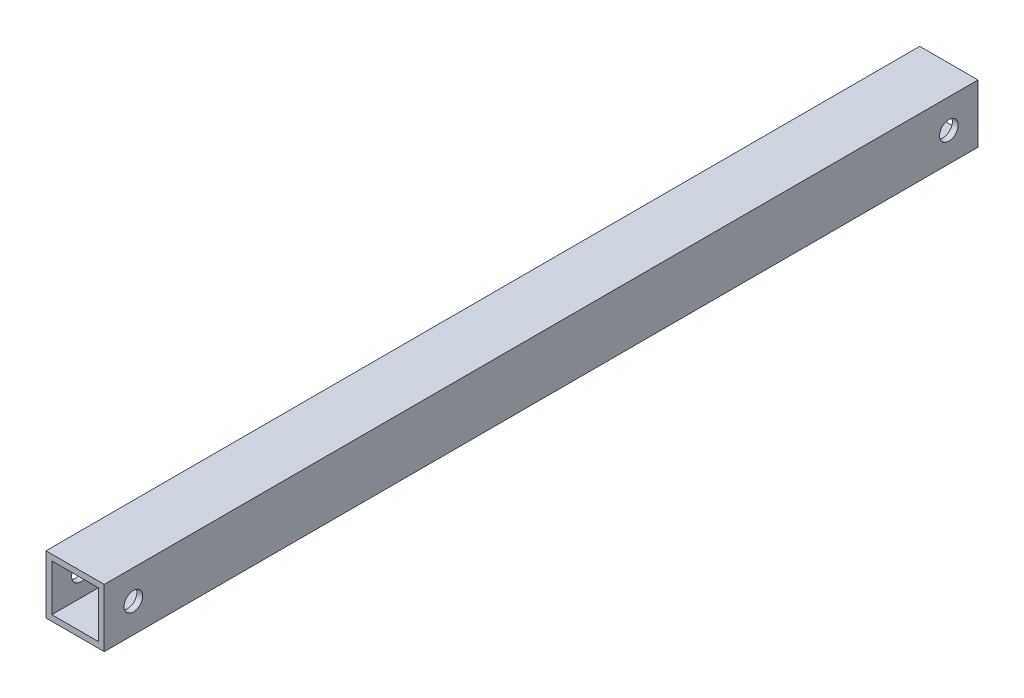
SolidWorks part; units mm, degrees
ref_plane "正面" through (0, 0, 0) normal (0, 0, 1) x (1, 0, 0)
ref_plane "平面" through (0, 0, 0) normal (0, 1, 0) x (1, 0, 0)
ref_plane "右側面" through (0, 0, 0) normal (1, 0, 0) x (0, 0, -1)
sketch "ｽｹｯﾁ1" plane through (0, 0, 0) normal (0, 0, 1) x (1, 0, 0)
  line L0 (-4, 4) -> (-4, -4)
  line L1 (-5, 5) -> (5, 5)
  line L2 (-5, 5) -> (-5, -5)
  line L3 (-5, -5) -> (5, -5)
  line L4 (5, 5) -> (5, -5)
  line L5 (-5, 5) -> (5, -5) construction
  line L6 (-5, -5) -> (5, 5) construction
  line L7 (-4, -4) -> (4, -4)
  line L8 (4, 4) -> (4, -4)
  line L9 (-4, 4) -> (4, 4)
  point P0 (0, 0)
  dimension "D1" = 10
  dimension "D2" = 10
  dimension "D3" = 1
extrude "ﾎﾞｽ - 押し出し1" add sketch "ｽｹｯﾁ1" along normal blind 150
sketch "ｽｹｯﾁ2" plane through (5, 0, 0) normal (1, 0, 0) x (0, 0, -1)
  line L0 (5.5, 0) -> (-5.5, 0) construction
  line L1 (-150, -5) -> (-150, 5) construction
  line L2 (0, 5.5) -> (0, -5.5) construction
  circle A0 centre (-145, 0) radius 1.6
  circle A1 centre (-5, 0) radius 1.6
  dimension "D1" = 3.2
  dimension "D2" = 3.2
  dimension "D3" = 5
  dimension "D4" = 5
extrude "ｶｯﾄ - 押し出し1" cut sketch "ｽｹｯﾁ2" against normal through all
